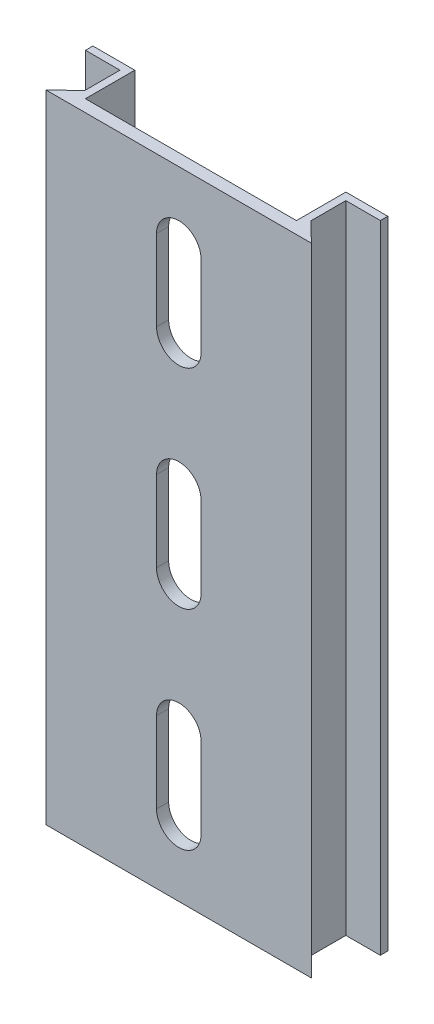
SolidWorks part; units mm, degrees
ref_plane "Front Plane" through (0, 0, 0) normal (0, 0, 1) x (1, 0, 0)
ref_plane "Top Plane" through (0, 0, 0) normal (0, 1, 0) x (1, 0, 0)
ref_plane "Right Plane" through (0, 0, 0) normal (1, 0, 0) x (0, 0, -1)
sketch "Sketch1" plane through (0, 0, 0) normal (0, 1, 0) x (1, 0, 0)
  line L0 (0, 0) -> (0, 1.4478)
  line L1 (-12.6365, 1.4478) -> (12.6365, 1.4478)
  line L2 (12.6365, 1.4478) -> (12.6365, 7.366)
  line L3 (12.6365, 7.366) -> (17.653, 7.366)
  line L4 (17.653, 7.366) -> (17.653, 6.477)
  line L5 (17.653, 6.477) -> (13.5255, 6.477)
  line L6 (13.5255, 6.477) -> (13.5255, 2.286)
  line L7 (13.5255, 2.286) -> (15.875, 0)
  line L8 (15.875, 0) -> (-15.875, 0)
  line L9 (-13.5255, 2.286) -> (-15.875, 0)
  line L10 (-13.5255, 6.477) -> (-13.5255, 2.286)
  line L11 (-17.653, 6.477) -> (-13.5255, 6.477)
  line L12 (-17.653, 7.366) -> (-17.653, 6.477)
  line L13 (-12.6365, 7.366) -> (-17.653, 7.366)
  line L14 (-12.6365, 1.4478) -> (-12.6365, 7.366)
  dimension "D1" = 15.875
  dimension "D2" = 13.5255
  dimension "D3" = 0.889
  dimension "D4" = 1.4478
  dimension "D5" = 7.366
  dimension "D6" = 0.889
  dimension "D7" = 2.286
  dimension "D8" = 17.653
extrude "Boss-Extrude1" add sketch "Sketch1" along normal mid plane 76.2 contours L1 L14 L13 L12 L11 L10 L9 L8 L0 | L8 L7 L6 L5 L4 L3 L2 L1 L0
sketch "Sketch2" plane through (0, 0, 0) normal (0, 0, 1) x (1, 0, 0)
  line L0 (0, -4.833) -> (0, 4.833) construction
  line L1 (-2.667, -4.833) -> (-2.667, 4.833)
  line L2 (2.667, -4.833) -> (2.667, 4.833)
  line L3 (-15.875, 0) -> (15.875, 0) construction
  line L4 (-15.875, 38.1) -> (-15.875, -38.1) construction
  line L5 (15.875, 38.1) -> (15.875, -38.1) construction
  arc A0 (-2.667, -4.833) -> (2.667, -4.833) centre (0, -4.833) ccw
  arc A1 (2.667, 4.833) -> (-2.667, 4.833) centre (0, 4.833) ccw
  point P3 (0, 0)
  point P15 (0, -7.5)
  point P16 (0, 7.5)
  dimension "D1" = 15
  dimension "D2" = 2.667
extrude "Cut-Extrude1" cut sketch "Sketch2" against normal through all
ref_plane "Plane1" through (0, 0, 0) normal (-1, 0, 0) x (0, 0, 1)
ref_plane "Plane2" through (0, 0, 0) normal (0, 1, 0) x (1, 0, 0)
pattern_linear "LPattern1" count 2 spacing 25 along (0, -1, 0) count 2 spacing 25 along (0, 1, 0) of "Cut-Extrude1"
